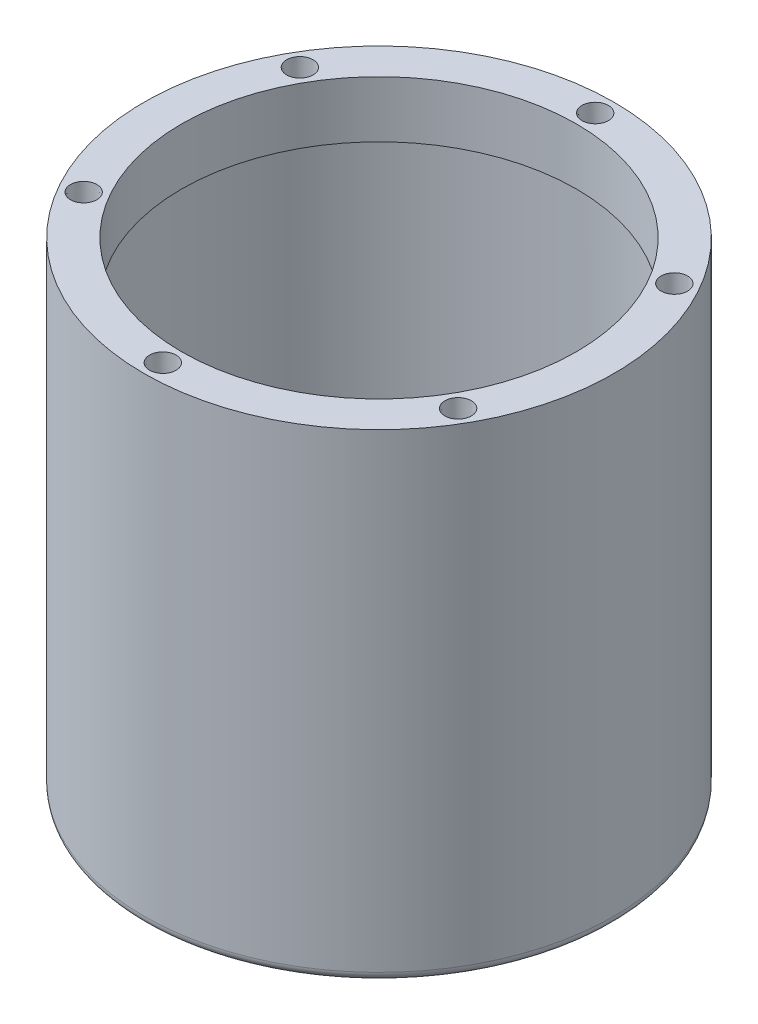
SolidWorks part; units mm, degrees
ref_plane "Front Plane" through (0, 0, 0) normal (0, 0, 1) x (1, 0, 0)
ref_plane "Top Plane" through (0, 0, 0) normal (0, 1, 0) x (1, 0, 0)
ref_plane "Right Plane" through (0, 0, 0) normal (1, 0, 0) x (0, 0, -1)
sketch "Sketch1" plane through (0, 0, 0) normal (0, 0, 1) x (1, 0, 0)
  line L0 (0, 0) -> (60.96, 0)
  line L1 (63.5, 0) -> (63.5, 127)
  line L2 (0, 0) -> (0, 2.54)
  line L3 (0, 2.54) -> (60.96, 2.54)
  line L4 (60.96, 2.54) -> (60.96, 127)
  line L6 (60.96, 127) -> (63.5, 127)
  line L7 (60.96, 0) -> (60.96, -2.54)
  arc A0 (63.5, 0) -> (60.96, -2.54) centre (60.96, 0) cw
  dimension "D1" = 63.5
  dimension "D2" = 127
  dimension "D3" = 60.96
  dimension "D4" = 2.54
  dimension "D5" = 2.54
revolve "Revolve1" add sketch "Sketch1" angle 360 about L2
sketch "Sketch2" plane through (0, 127, 0) normal (0, 1, 0) x (1, 0, 0)
  circle A0 centre (0, 0) radius 60.96
  circle A1 centre (0, 0) radius 53.34
  circle A2 centre (0, 0) radius 60.96 construction
  circle A3 centre (0, 0) radius 63.5 construction
  dimension "D1" = 10.16
  dimension "D2" = 7.62
  dimension "D3" = 106.68
extrude "Boss-Extrude1" add sketch "Sketch2" against normal blind 15.24
sketch "Sketch5" plane through (0, 127, 0) normal (0, 1, 0) x (1, 0, 0)
  line L0 (0, 0) -> (0, -63.5) construction
  circle A1 centre (0, 0) radius 63.5 construction
  circle A2 centre (-50.5932, -29.21) radius 5.08
  circle A6 centre (0, -58.42) radius 5.08
  circle A8 centre (0, 0) radius 53.34 construction
  circle A9 centre (-50.5932, 29.21) radius 5.08
  circle A10 centre (0, 58.42) radius 5.08
  circle A11 centre (50.5932, 29.21) radius 5.08
  circle A12 centre (50.5932, -29.21) radius 5.08
  dimension "D1" = 6
hole_wizard "1/16 NPT Tapped Hole2" positions "3DSketch7" profile "Sketch7" size "1/16" standard "ANSI Inch"
sketch3d "3DSketch7"
  point P0 (0, 127, -58.42)
  point P3 (-50.5932, 127, -29.21)
  point P6 (-50.5932, 127, 29.21)
  point P9 (0, 127, 58.42)
  point P12 (50.5932, 127, 29.21)
  point P15 (50.5932, 127, -29.21)
cosmetic thread "Hole Thread7" parameters "D1"=6.858, "D2"=7.9358
cosmetic thread "Hole Thread8" parameters "D1"=6.858, "D2"=7.9358
cosmetic thread "Hole Thread9" parameters "D1"=6.858, "D2"=7.9358
cosmetic thread "Hole Thread10" parameters "D1"=6.858, "D2"=7.9358
cosmetic thread "Hole Thread11" parameters "D1"=6.858, "D2"=7.9358
cosmetic thread "Hole Thread12" parameters "D1"=6.858, "D2"=7.9358
sketch "Sketch7" plane through (0, 127, -58.42) normal (1, 0, 0) x (0, 0, 1)
  line L0 (0, 0) -> (0, 13.5307)
  line L1 (3.0734, 11.684) -> (0, 13.5307)
  line L2 (-3.0734, 11.684) -> (0, 13.5307) construction
  line L3 (3.0734, 11.684) -> (3.0734, 6.858)
  line L4 (3.0734, 6.858) -> (3.3648, 6.858)
  line L5 (3.3648, 6.858) -> (3.5701, 0)
  line L6 (-3.3648, 6.858) -> (-3.5701, 0) construction
  line L7 (3.5701, 0) -> (0, 0)
  line L8 (0, -6.35) -> (0, 107.95) construction
  line L11 (-3.0734, 6.858) -> (-3.3648, 6.858) construction
  dimension "Tap Drill Dia." = 6.1468
  dimension "Tap Drill Depth" = 11.684
  dimension "Thread Dia." = 7.1403
  dimension "Thread Angle" = 3.43
  dimension "Thread Depth" = 6.858
  dimension "Drill Angle" = 118
sketch "Sketch8" plane through (0, 0, 0) normal (0, -1, 0) x (1, 0, 0)
  circle A0 centre (0, 0) radius 25.4
  dimension "D1" = 50.8
extrude "Cut-Extrude1" cut sketch "Sketch8" against normal blind 2.54
